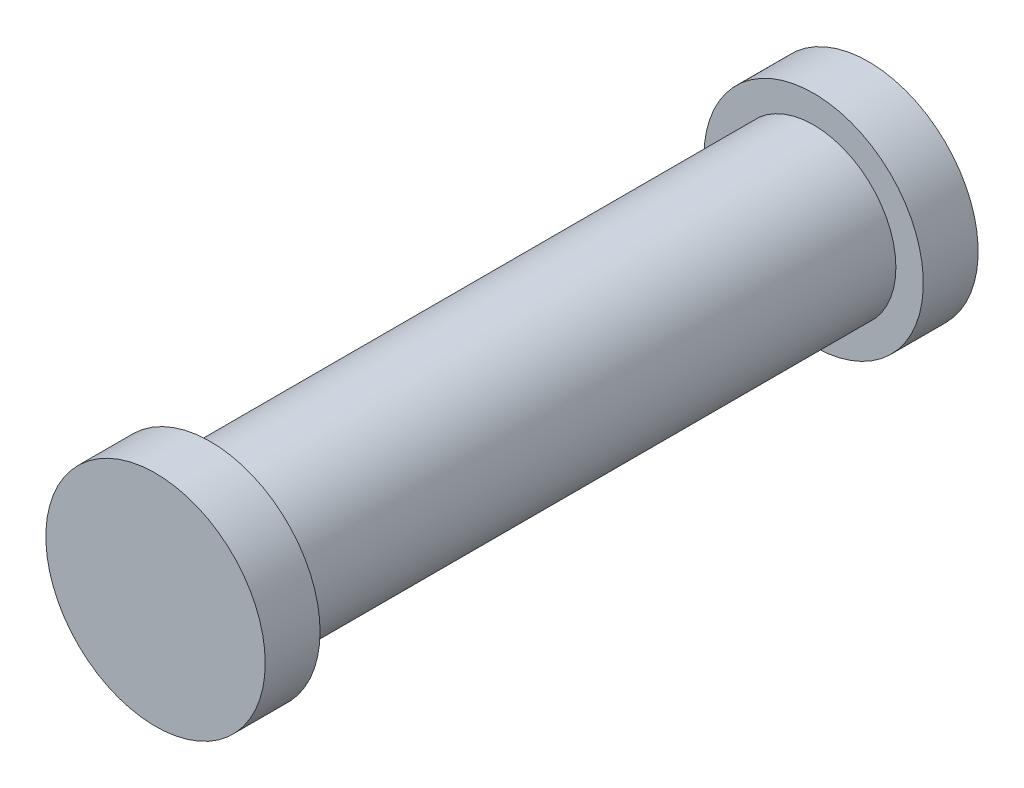
SolidWorks part; units mm, degrees
ref_plane "前视基准面" through (0, 0, 0) normal (0, 0, 1) x (1, 0, 0)
ref_plane "上视基准面" through (0, 0, 0) normal (0, 1, 0) x (1, 0, 0)
ref_plane "右视基准面" through (0, 0, 0) normal (1, 0, 0) x (0, 0, -1)
sketch "草图1" plane through (0, 0, 0) normal (0, 0, 1) x (1, 0, 0)
  circle A0 centre (0, 0) radius 30
extrude "凸台-拉伸1" add sketch "草图1" along normal blind 220
sketch "草图2" plane through (0, 0, 220) normal (0, 0, 1) x (1, 0, 0)
  circle A0 centre (0, 0) radius 40
extrude "凸台-拉伸2" add sketch "草图2" along normal blind 20
sketch "草图3" plane through (0, 0, 0) normal (0, 0, -1) x (-1, 0, 0)
  circle A0 centre (0, 0) radius 40
extrude "凸台-拉伸3" add sketch "草图3" along normal blind 20
scale "缩放比例1" scale about origin uniform scaling yes scale factor 0.345
